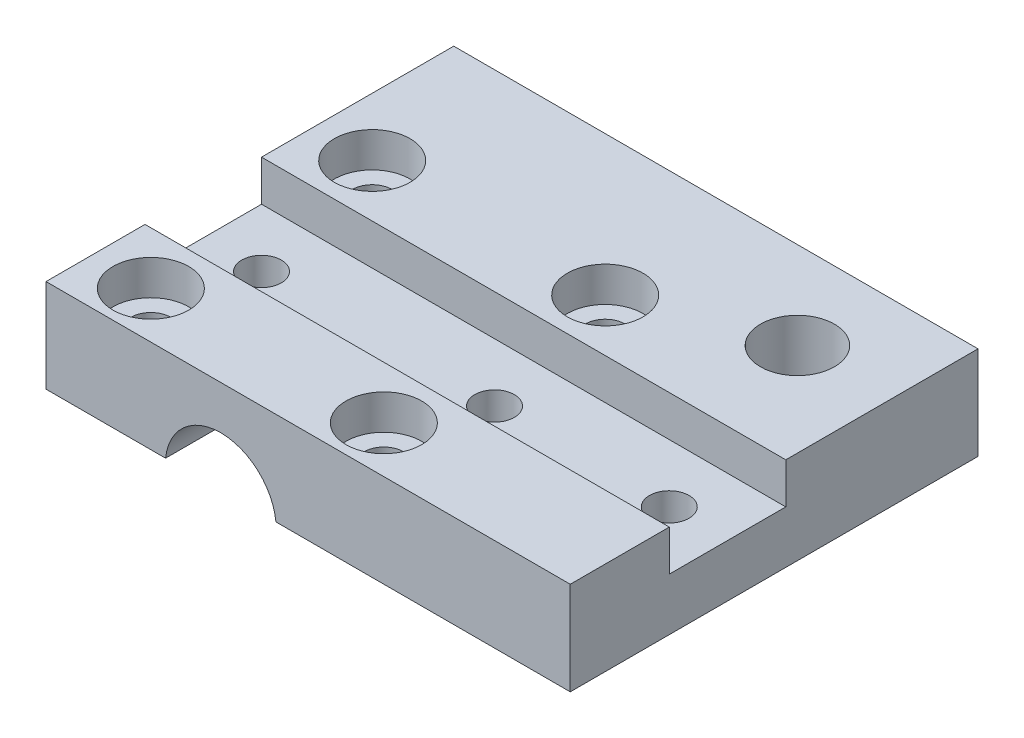
SolidWorks part; units mm, degrees
ref_plane "Front" through (0, 0, 0) normal (0, 0, 1) x (1, 0, 0)
ref_plane "Top" through (0, 0, 0) normal (0, 1, 0) x (1, 0, 0)
ref_plane "Right" through (0, 0, 0) normal (1, 0, 0) x (0, 0, -1)
sketch "Sketch1" plane through (0, 0, 0) normal (0, 0, 1) x (1, 0, 0)
  line L0 (30, 0.5) -> (30, 5.5)
  line L1 (-15, 0.5) -> (-4.7362, 0.5)
  line L2 (-15, 0.5) -> (-15, 8.5)
  line L3 (-15, 8.5) -> (30, 8.5)
  line L4 (30, 5.5) -> (30, 8.5)
  line L5 (7.5, 0.5) -> (7.5, 8.5) construction
  line L6 (-7.5, 0.5) -> (-7.5, 8.5) construction
  line L7 (0, 0) -> (0, 8.5) construction
  line L8 (4.7362, 0.5) -> (30, 0.5)
  arc A0 (4.7362, 0.5) -> (-4.7362, 0.5) centre (0, 0) ccw
  dimension "D2" = 9.525
  dimension "D1" = 0.5
  dimension "D3" = 15
  dimension "D4" = 3
  dimension "D5" = 8
  dimension "D6" = 15
  dimension "D7" = 45
  dimension "D8" = 90
extrude "Boss-Extrude1" add sketch "Sketch1" along normal mid plane 35
sketch "Sketch2" plane through (0, 8.5, 0) normal (0, 1, 0) x (1, 0, 0)
  line L0 (22, 10) -> (0, 10) construction
  circle A0 centre (22, 10) radius 3.175
  circle A1 centre (22, 10) radius 8
  dimension "D3" = 6.35
  dimension "D4" = 16
  dimension "D1" = 22
  dimension "D2" = 10
extrude "Cut-Extrude1" cut sketch "Sketch2" against normal up to next
sketch "Sketch3" plane through (0, 8.5, 0) normal (0, 1, 0) x (1, 0, 0)
  line L0 (-15, -4) -> (30, -4)
  line L1 (-15, -17.5) -> (-15, 17.5) construction
  line L2 (30, -17.5) -> (30, 17.5) construction
  circle A0 centre (22, 10) radius 3.175 construction
  dimension "D1" = 14
extrude "Cut-Extrude-Thin2" cut sketch "Sketch3" against normal blind 3.5 thin thin type mid plane wall 10
sketch "Sketch4" plane through (0, 8.5, 0) normal (0, 1, 0) x (1, 0, 0)
  line L0 (0, -4) -> (0, 0) construction
  line L1 (10, -13.5) -> (-10, -13.5) construction
  line L2 (10, -13.5) -> (10, 5.5) construction
  line L3 (10, 5.5) -> (-10, 5.5) construction
  line L4 (-10, -13.5) -> (-10, 5.5) construction
  line L5 (10, -13.5) -> (-10, 5.5) construction
  line L6 (10, 5.5) -> (-10, -13.5) construction
  line L7 (30, -17.5) -> (-15, -17.5) construction
  line L10 (-15, 1) -> (30, 1) construction
  point P0 (0, -4)
  dimension "D1" = 20
  dimension "D2" = 4
  dimension "D3" = 4.5
hole_wizard "CBORE for M3 SHCS1" positions "Sketch6" profile "Sketch7" counterbore size "M3" standard "Ansi Metric" end condition through all
sketch "Sketch6" plane through (0, 8.5, 0) normal (0, 1, 0) x (-1, 0, 0)
  point P0 (-10, 13.5)
  point P1 (-10, -5.5)
  point P4 (10, -5.5)
  point P7 (10, 13.5)
sketch "Sketch7" plane through (10, 8.5, 13.5) normal (1, 0, 0) x (0, 0, 1)
  line L0 (0, 0) -> (0, 8)
  line L1 (0, 8) -> (1.7, 8)
  line L3 (1.7, 8) -> (1.7, 3)
  line L4 (1.7, 3) -> (3.25, 3)
  line L5 (3.25, 3) -> (3.25, 0)
  line L7 (3.25, 0) -> (0, 0)
  line L11 (0, -6.35) -> (0, 107.95) construction
  dimension "Thru Hole Dia." = 3.4
  dimension "Thru Hole Depth" = 8
  dimension "C'Bore Dia." = 6.5
  dimension "C'Bore Depth" = 3
sketch "Sketch8" plane through (0, 5, 0) normal (0, 1, 0) x (1, 0, 0)
  line L0 (-15, -4) -> (30, -4) construction
  line L1 (-15, -9) -> (-15, 1) construction
  line L2 (30, 1) -> (30, -9) construction
  line L3 (10, -13.5) -> (10, 5.5) construction
  point P6 (-10, -4)
  point P7 (15, -4)
  point P8 (25, -4)
  dimension "D1" = 5
  dimension "D2" = 5
  dimension "D3" = 5
hole_wizard "M3 Clearance Hole1" positions "Sketch10" profile "Sketch9" hole size "M3" standard "Ansi Metric" end condition through all
sketch "Sketch10" plane through (0, 5, 0) normal (0, 1, 0) x (-1, 0, 0)
  line L0 (15, 4) -> (-30, 4) construction
  line L1 (-10, 13.5) -> (-10, -5.5) construction
  point P0 (-10, 4)
  point P1 (-25, 4)
  point P4 (10, 4)
sketch "Sketch9" plane through (10, 5, 4) normal (1, 0, 0) x (0, 0, 1)
  line L0 (0, 0) -> (0, 4.5)
  line L1 (0, 4.5) -> (1.7, 4.5)
  line L2 (1.7, 4.5) -> (1.7, 0)
  line L5 (1.7, 0) -> (0, 0)
  line L11 (0, -6.35) -> (0, 107.95) construction
  dimension "Thru Hole Dia." = 3.4
  dimension "Thru Hole Depth" = 4.5
sketch "Sketch11" plane through (0, 0.5, 0) normal (0, -1, 0) x (1, 0, 0)
  line L0 (10, 13.5) -> (10, -5.5) construction
  circle A0 centre (-10, 4) radius 4
  circle A1 centre (10, 4) radius 4
  circle A2 centre (25, 4) radius 4
  dimension "D1" = 8
extrude "Cut-Extrude2" cut sketch "Sketch11" against normal blind 1
